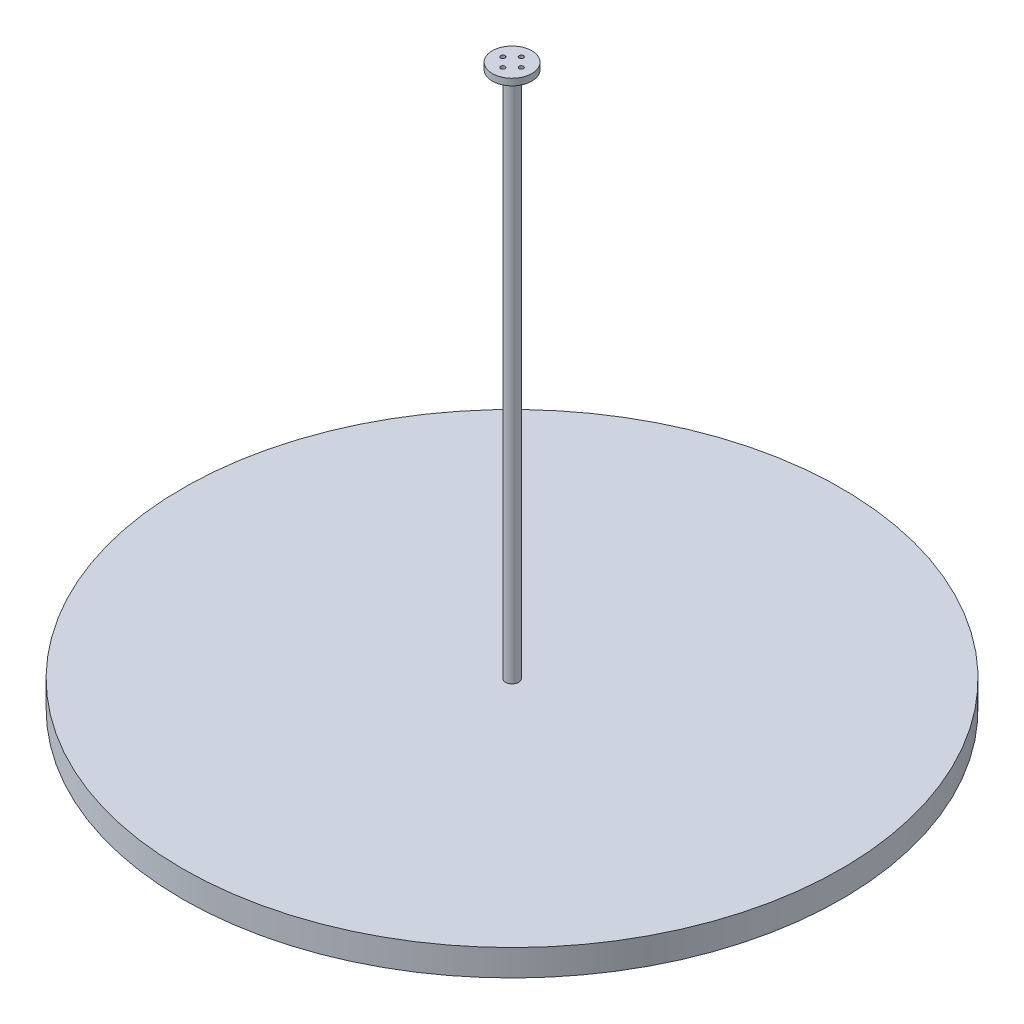
SolidWorks part; units mm, degrees
ref_plane "前视基准面" through (0, 0, 0) normal (0, 0, 1) x (1, 0, 0)
ref_plane "上视基准面" through (0, 0, 0) normal (0, 1, 0) x (1, 0, 0)
ref_plane "右视基准面" through (0, 0, 0) normal (1, 0, 0) x (0, 0, -1)
sketch "草图1" plane through (0, 0, 0) normal (0, 1, 0) x (1, 0, 0)
  circle A0 centre (0, 0) radius 250
  dimension "D1" = 500
extrude "凸台-拉伸1" add sketch "草图1" along normal blind 20
sketch "草图2" plane through (0, 20, 0) normal (0, 1, 0) x (1, 0, 0)
  circle A0 centre (0, 0) radius 5
  dimension "D1" = 10
extrude "凸台-拉伸2" add sketch "草图2" along normal blind 400
sketch "草图3" plane through (0, 420, 0) normal (0, 1, 0) x (1, 0, 0)
  circle A0 centre (0, 0) radius 15
  dimension "D1" = 30
extrude "凸台-拉伸3" add sketch "草图3" along normal blind 5
sketch "草图4" plane through (0, 425, 0) normal (0, 1, 0) x (1, 0, 0)
  line L0 (-15, 0) -> (15, 0) construction
  circle A0 centre (0, 0) radius 15 construction
  circle A1 centre (-7, 0) radius 1.65
  dimension "D1" = 3.3
  dimension "D2" = 7
extrude "切除-拉伸1" cut sketch "草图4" against normal blind 5
pattern_circular "阵列(圆周)1" count 4 over 360 about axis through (0, 0, 0) along (0, 1, 0) of "切除-拉伸1"
